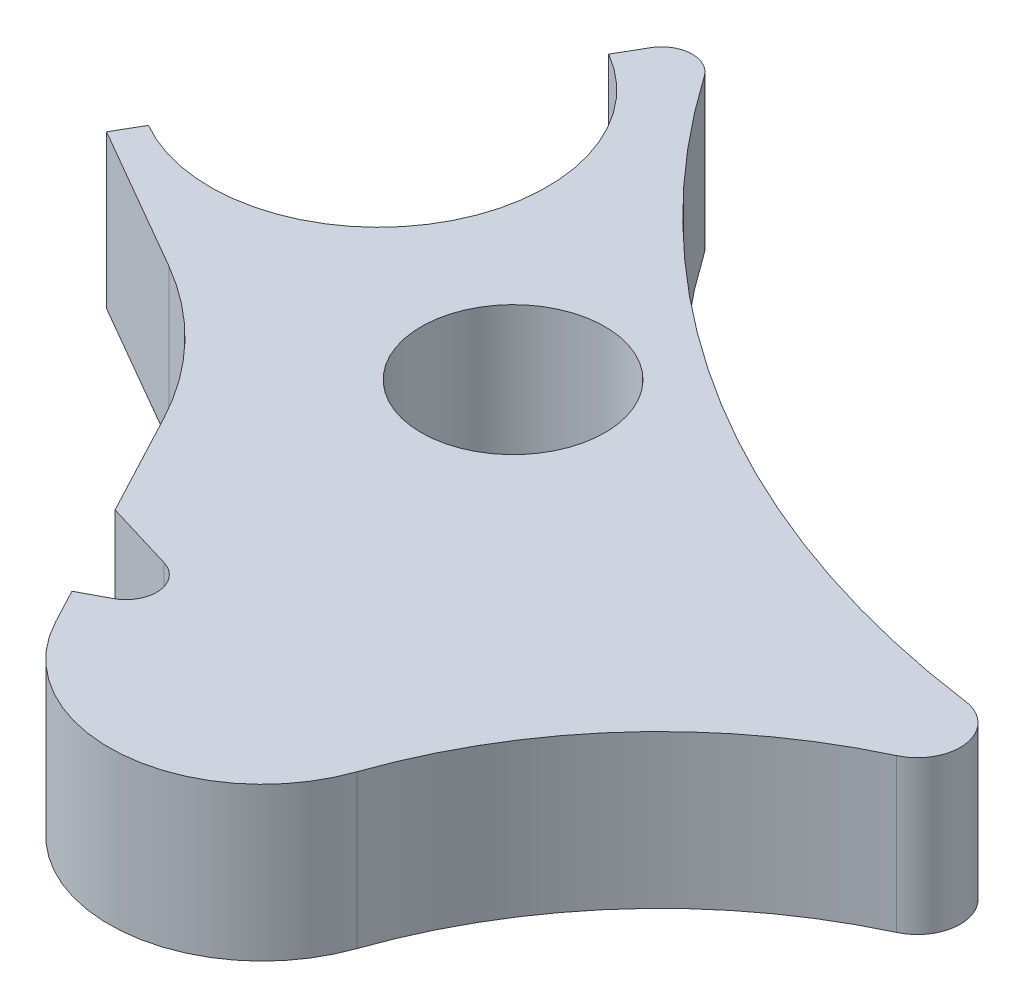
SolidWorks part; units mm, degrees
material "Q355"
ref_plane "前视基准面" through (0, 0, 0) normal (0, 0, 1) x (1, 0, 0)
ref_plane "上视基准面" through (0, 0, 0) normal (0, 1, 0) x (1, 0, 0)
ref_plane "右视基准面" through (0, 0, 0) normal (1, 0, 0) x (0, 0, -1)
sketch "草图1" plane through (0, 0, 0) normal (0, 1, 0) x (1, 0, 0)
  line L0 (0, 0) -> (-51.9615, 30) construction
  line L2 (-22.5, -35) -> (-14.0639, -50.9007) construction
  line L6 (-6.0964, -65.918) -> (-1.6796, -63.5746)
  line L7 (-23.098, -33.8728) -> (-14.0639, -50.9007)
  line L8 (0, 0) -> (0, -118.0385) construction
  line L9 (-38.2115, 53.8157) -> (-65.7115, 6.1843) construction
  line L10 (-44.1835, -12.0184) -> (-68.2115, 1.8542)
  line L11 (-68.2115, 1.8542) -> (-65.7115, 6.1843)
  line L13 (-16.25, -28.1458) -> (-68.2115, 1.8542) construction
  line L14 (-6.0964, -65.918) -> (-3.0198, -71.7168)
  line L16 (-14.0639, -50.9007) -> (-2.5768, -54.3715)
  line L17 (-31.673, 65.1408) -> (-38.2115, 53.8157)
  circle A0 centre (0, 0) radius 15
  arc A3 (-31.673, 65.1408) -> (82.4424, -8.5637) centre (103.9823, 149.9797) ccw
  arc A5 (-1.6796, -63.5746) -> (-2.5768, -54.3715) centre (-4.0229, -59.1578) ccw
  arc A6 (84.4602, -21.8433) -> (82.4424, -8.5637) centre (81.5, -15.5) ccw
  arc A7 (-3.0198, -71.7168) -> (42.6898, -68.1757) centre (19.0644, -60) ccw
  arc A8 (84.4602, -21.8433) -> (42.6898, -68.1757) centre (118.291, -94.338) ccw
  arc A9 (-65.7115, 6.1843) -> (-38.2115, 53.8157) centre (-51.9615, 30) ccw
  arc A13 (-23.098, -33.8728) -> (-44.1835, -12.0184) centre (-71.6835, -59.6498) ccw
  dimension "D1" = 15
  dimension "D4" = 15.5
  dimension "D7" = 160
  dimension "D14" = 35
  dimension "D6" = 13.0771
  dimension "D8" = 7
  dimension "D9" = 62.4356
  dimension "D10" = 22.5
  dimension "D11" = 35
  dimension "D15" = 5
  dimension "D16" = 50
  dimension "D17" = 60
  dimension "D18" = 17
  dimension "D19" = 120
  dimension "D21" = 80
  dimension "D23" = 55
  dimension "D22" = 55
  dimension "D3" = 5
  dimension "D5" = 81.5
  dimension "D20" = 60
  dimension "D25" = 32.5
extrude "凸台-拉伸1" add sketch "草图1" along normal mid plane 25
fillet "圆角1" radius 5 1 edges at (-31.673, 0, -65.1408)
